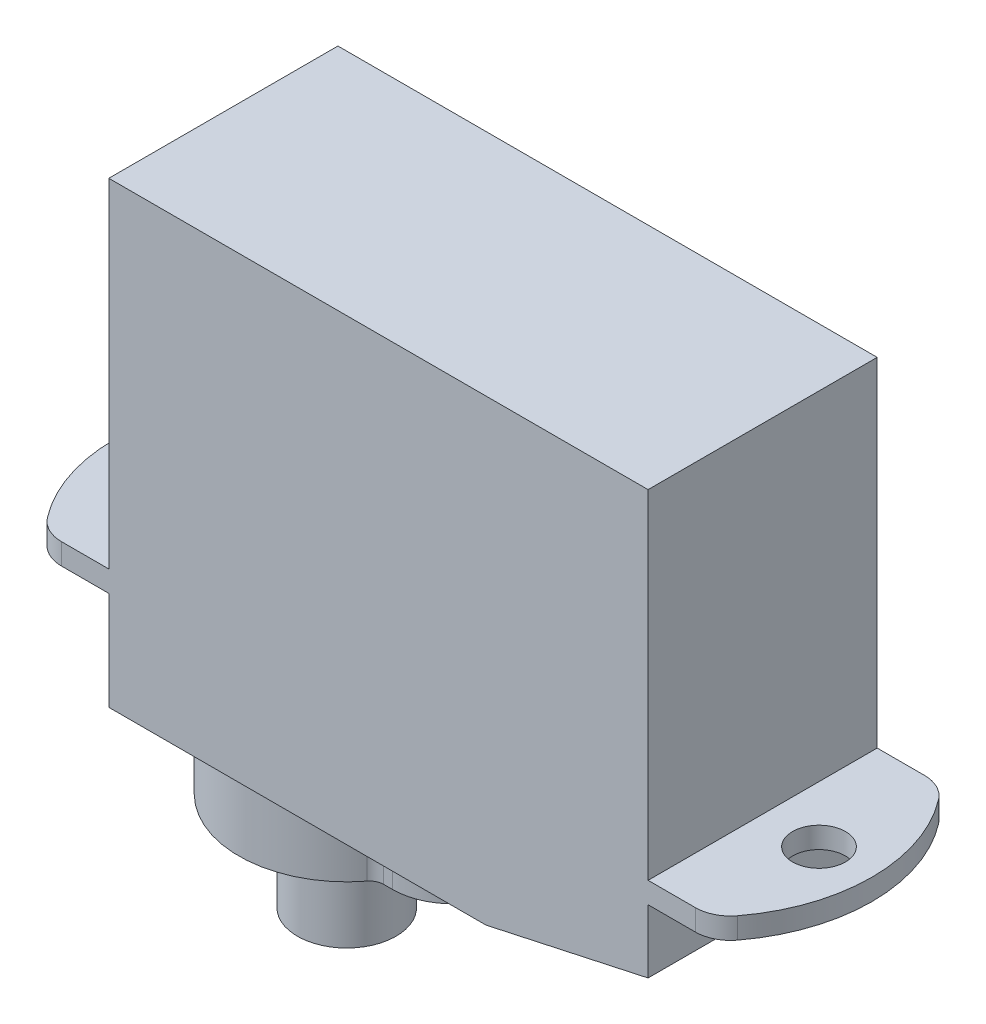
SolidWorks part; units mm, degrees
ref_plane "Front Plane" through (0, 0, 0) normal (0, 0, 1) x (1, 0, 0)
ref_plane "Top Plane" through (0, 0, 0) normal (0, 1, 0) x (1, 0, 0)
ref_plane "Right Plane" through (0, 0, 0) normal (1, 0, 0) x (0, 0, -1)
sketch "Sketch1" plane through (0, 0, 0) normal (0, 1, 0) x (1, 0, 0)
  line L1 (9.7155, -4.1275) -> (-9.7155, -4.1275)
  line L2 (9.7155, -4.1275) -> (9.7155, 4.1275)
  line L3 (9.7155, 4.1275) -> (-9.7155, 4.1275)
  line L4 (-9.7155, -4.1275) -> (-9.7155, 4.1275)
  line L5 (9.7155, -4.1275) -> (-9.7155, 4.1275) construction
  line L6 (9.7155, 4.1275) -> (-9.7155, -4.1275) construction
  point P0 (0, 0)
  dimension "D1" = 19.431
  dimension "D2" = 8.255
extrude "Boss-Extrude1" add sketch "Sketch1" along normal blind 16.51
ref_plane "Plane1" through (0, 4.318, 0) normal (0, 1, 0) x (1, 0, 0)
sketch "Sketch2" plane through (0, 4.318, 0) normal (0, 1, 0) x (1, 0, 0)
  line L0 (9.7155, -4.1275) -> (9.7155, 4.1275) construction
  line L1 (-9.7155, 4.1275) -> (-9.7155, -4.1275) construction
  line L2 (9.7155, -4.1275) -> (9.7155, 4.1275)
  line L3 (-9.7155, 4.1275) -> (-9.7155, -4.1275)
  line L4 (0, 0) -> (0, 6.6742) construction
  line L5 (9.7155, 4.1275) -> (11.4179, 4.1275)
  line L6 (9.7155, -4.1275) -> (11.4179, -4.1275)
  line L7 (-9.7155, -4.1275) -> (-11.4179, -4.1275)
  line L8 (-9.7155, 4.1275) -> (-11.4179, 4.1275)
  arc A0 (12.4281, 3.6272) -> (12.4281, -3.6272) centre (7.6676, 0) cw
  arc A1 (-12.4281, 3.6272) -> (-12.4281, -3.6272) centre (-7.6676, 0) ccw
  circle A2 centre (11.7475, 0) radius 0.9525
  circle A3 centre (-11.7475, 0) radius 0.9525
  arc A4 (-12.4281, 3.6272) -> (-11.4179, 4.1275) centre (-11.4179, 2.8575) cw
  arc A5 (-11.4179, -4.1275) -> (-12.4281, -3.6272) centre (-11.4179, -2.8575) cw
  arc A6 (11.4179, -4.1275) -> (12.4281, -3.6272) centre (11.4179, -2.8575) ccw
  arc A7 (11.4179, 4.1275) -> (12.4281, 3.6272) centre (11.4179, 2.8575) cw
  point P19 (-12.0015, 4.1275)
  point P22 (-12.0015, -4.1275)
  point P25 (12.0015, -4.1275)
  point P28 (12.0015, 4.1275)
  dimension "D2" = 3.937
  dimension "D3" = 21.59
  dimension "D4" = 1.905
  dimension "D5" = 1.27
  dimension "D1" = 2.286
extrude "Boss-Extrude2" add sketch "Sketch2" against normal blind 0.762
sketch "Sketch3" plane through (0, 0, 4.1275) normal (0, 0, 1) x (1, 0, 0)
  line L0 (9.7155, 16.51) -> (9.7155, 1.27) construction
  line L1 (9.7155, 3.556) -> (9.7155, 0) construction
  line L2 (9.7155, 0) -> (3.8735, 0)
  line L3 (-9.7155, 0) -> (9.7155, 0) construction
  line L4 (9.7155, 1.27) -> (3.8735, 0)
  line L5 (9.7155, 1.27) -> (9.7155, 0)
  dimension "D1" = 15.24
  dimension "D2" = 5.842
extrude "Cut-Extrude1" cut sketch "Sketch3" against normal through all
sketch "Sketch4" plane through (0, 0, 0) normal (0, -1, 0) x (1, 0, 0)
  line L0 (-9.7155, 4.1275) -> (-9.7155, -4.1275) construction
  line L1 (-1.4605, 2.159) -> (-1.7782, 2.159)
  line L2 (-1.4605, -2.159) -> (-1.7782, -2.159)
  arc A0 (-2.1819, 2.3587) -> (-2.1819, -2.3587) centre (-5.2705, 0) ccw
  arc A1 (-1.4605, -2.159) -> (-1.4605, 2.159) centre (-1.4605, 0) ccw
  arc A2 (-1.7782, -2.159) -> (-2.1819, -2.3587) centre (-1.7782, -2.667) ccw
  arc A3 (-1.7782, 2.159) -> (-2.1819, 2.3587) centre (-1.7782, 2.667) cw
  dimension "D1" = 7.7724
  dimension "D3" = 4.318
  dimension "D5" = 0.508
  dimension "D2" = 4.445
  dimension "D4" = 3.81
extrude "Boss-Extrude3" add sketch "Sketch4" along normal blind 2.54
sketch "Sketch5" plane through (0, -2.54, 0) normal (0, -1, 0) x (1, 0, 0)
  arc A0 (-2.1819, 2.3587) -> (-2.1819, -2.3587) centre (-5.2705, 0) ccw construction
  arc A1 (-2.1819, 2.3587) -> (-2.1819, -2.3587) centre (-5.2705, 0) ccw construction
  circle A2 centre (-5.2705, 0) radius 1.778
  dimension "D1" = 3.556
extrude "Boss-Extrude4" add sketch "Sketch5" along normal blind 3.556
